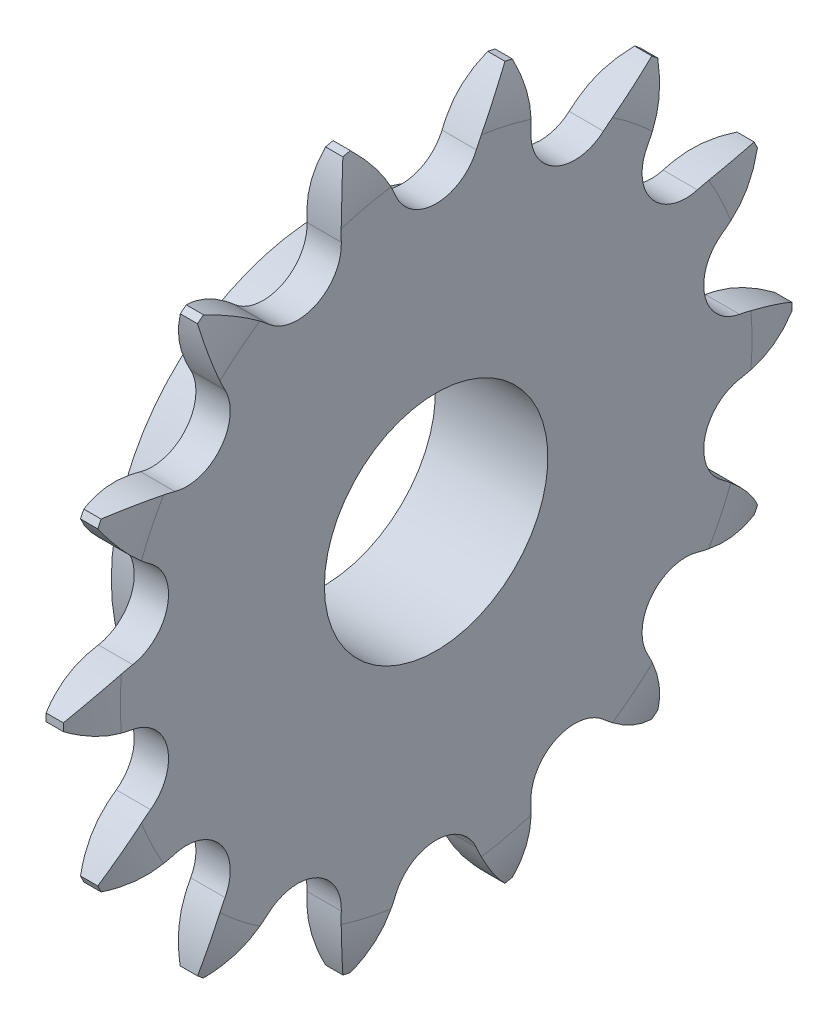
SolidWorks part; units mm, degrees
ref_plane "Plane1" through (0, 0, 0) normal (0, 0, 1) x (1, 0, 0)
ref_plane "Plane2" through (0, 0, 0) normal (0, 1, 0) x (1, 0, 0)
ref_plane "Plane3" through (0, 0, 0) normal (1, 0, 0) x (0, 0, -1)
sketch "Clipboard" plane through (0, 0, 0) normal (0, 1, 0) x (1, 0, 0)
  line L0 (0, 0) -> (12.3228, -3.0724)
  line L1 (-15, 0) -> (100, 0) construction
  line L2 (0, 0) -> (-0.5049, 0.5707)
  line L3 (0, 0) -> (-11.863, 4.5341)
  line L4 (0, 0) -> (3.0079, 0.75)
  line L5 (0, 0) -> (-5.6217, -2.0967)
  line L6 (0, 0) -> (-2.5441, -1.7165)
  line L7 (-0.5049, 0.5707) -> (5.2911, 2.1237)
  line L8 (-76.2, 38.1) -> (-73.4, 38.1)
  line L9 (-73.2427, 39.6204) -> (-72.6435, 39.6525)
  line L10 (-73.1375, 10.4807) -> (-66.1375, 10.4807)
  circle A0 centre (0, 0) radius 3.875
  circle A1 centre (0, 0) radius 19
  circle A2 centre (0, 0) radius 19
  dimension "Dr" = 7.75
  dimension "MHD" = 38
  dimension "Hub_dia" = 38
  dimension "Num_teeth" = 14
  dimension "Pitch" = 12.7
  dimension "Width" = 3.1
  dimension "Side_relief" = 0.762
  dimension "Side_radius" = 12.7
  dimension "Overall_len" = 6
  dimension "Show_teeth" = 14
  dimension "Thickness" = 3.069
  dimension "OAL" = 6.0005
  dimension "T_dim" = 2.8
  dimension "Fillet_rad" = 0.6
  dimension "Face_width" = 3.069
  dimension "Num_strands" = 1
  dimension "Transv_pitch" = 7
  dimension "Plate_wid" = 9.91
sketch "BasProSke" plane through (0, 0, 0) normal (0, 1, 0) x (1, 0, 0)
  line L0 (-10, 0) -> (60, 0) construction
  line L1 (0, 0) -> (0, 28.2662)
  line L2 (0, 0) -> (3.069, 0)
  line L3 (3.069, 0) -> (3.069, 28.2662)
  line L4 (2.307, 32.5991) -> (0.762, 32.5991)
  arc A0 (0, 28.2662) -> (0.762, 32.5991) centre (12.7, 28.2662) cw
  arc A1 (3.069, 28.2662) -> (2.307, 32.5991) centre (-9.631, 28.2662) ccw
  dimension "Thickness" = 3.069
  dimension "D1" = 12.7
  dimension "G1" = 0.762
  dimension "G2" = 0.762
  dimension "Diameter" = 65.1983
revolve "Base-Revolve" add sketch "BasProSke" angle 360 about L0
sketch "TooCutSke" plane through (0, 0, 0) normal (1, 0, 0) x (0, 0, -1)
  line L0 (0, 28.5754) -> (3.5969, 27.0327) construction
  line L1 (0, 0) -> (0, 107) construction
  line L2 (0, 28.5754) -> (-10, 28.5754) construction
  line L3 (0, 28.5754) -> (-3.5969, 27.0327) construction
  arc A0 (3.5969, 27.0327) -> (7.3646, 32.2694) centre (17.2722, 21.1674) cw
  arc A1 (3.5969, 27.0327) -> (-3.5969, 27.0327) centre (0, 28.5754) cw
  arc A2 (-3.5969, 27.0327) -> (-7.3646, 32.2694) centre (-17.2722, 21.1674) ccw
  arc A3 (7.3646, 32.2694) -> (-7.3646, 32.2694) centre (0, 0) ccw
  dimension "R1" = 3.9137
  dimension "R2" = 14.88
  dimension "Overcut" = 33.0991
  dimension "Seat_radius" = 28.5754
  dimension "X" = 133.571
extrude "ToothCut" cut sketch "TooCutSke" along normal through all
pattern_circular "TeethCuts" count 14 every 25.714 about axis through (-10, 0, 0) along (1, 0, 0) of "ToothCut"
sketch "HubNeaOneSke" plane through (0, 0, 0) normal (-1, 0, 0) x (0, 0, 1)
  circle A0 centre (0, 0) radius 19
  dimension "Diameter" = 38
extrude "HubNearOne" add sketch "HubNeaOneSke" along normal blind 7
fillet "HubNearOneFillet" radius 0.6 1 edges at (0, 0, -19)
sketch "HubNeaBotSke" plane through (0, 0, 0) normal (-1, 0, 0) x (0, 0, 1)
  circle A0 centre (0, 0) radius 19
  dimension "Diameter" = 38
extrude "HubNearBoth" [suppressed] add sketch "HubNeaBotSke" along normal blind 1.4657
fillet "HubNearBothFillet" [suppressed] radius 0.6
ref_plane "FarPln" through (3.069, 0, 0) normal (1, 0, 0) x (0, 0, -1)
sketch "HubFarSke" plane through (3.069, 0, 0) normal (1, 0, 0) x (0, 0, -1)
  circle A0 centre (0, 0) radius 19
  dimension "Diameter" = 38
extrude "HubFar" [suppressed] add sketch "HubFarSke" along normal blind 1.4657
fillet "HubFarFillet" [suppressed] radius 0.6
sketch "BorSke" plane through (0, 0, 0) normal (1, 0, 0) x (0, 0, -1)
  circle A0 centre (0, 0) radius 10
  dimension "Diameter" = 20
extrude "Bore" cut sketch "BorSke" along normal through all both and the other way through all
sketch "KeySke" plane through (0, 0, 0) normal (1, 0, 0) x (0, 0, -1)
  line L0 (-3, 0) -> (-3, 12.8)
  line L1 (-3, 12.8) -> (3, 12.8)
  line L2 (3, 12.8) -> (3, 0)
  line L3 (0, 0) -> (0, 34) construction
  line L4 (-3, 0) -> (3, 0)
  dimension "Offset" = 12.8
  dimension "Width" = 6
extrude "Keyway" [suppressed] cut sketch "KeySke" along normal mid plane 12.001
pattern_circular "Keyway2" [suppressed] count 2 every 90 about axis through (-10, 0, 0) along (1, 0, 0)
equation "' \"Pitch@Clipboard\" = 12.7"
equation "' \"Num_strands@Clipboard\" = 1"
equation "' \"Num_teeth@Clipboard\" = 9"
equation "' \"Hub_dia@Clipboard\" = 50"
equation "' \"Overall_len@Clipboard\" = 3"
equation "' \"Diameter@BorSke\" = 12"
equation "' \"T_dim@Clipboard\" = 1"
equation "' \"Width@KeySke\" = 2"
equation "' \"Dr@Clipboard\" = 8.51"
equation "' \"Face_width@Clipboard\" = 7.2"
equation "' \"Side_radius@Clipboard\" = 12.7"
equation "' \"Side_relief@Clipboard\" = 1.27"
equation "' \"Transv_pitch@Clipboard\" = 13.92"
equation "' \"Show_teeth@Clipboard\" = 9"
equation "' \"Fillet_rad@Clipboard\" = 0.6"
equation "' \"Plate_wid@Clipboard\" = 11.8"
equation "\"Num_teeth@Clipboard\" = int( \"Num_teeth@Clipboard\" )"
equation "\"Num_teeth@Clipboard\" = ((sgn( \"Num_teeth@Clipboard\" - 5.0)+1)*( \"Num_teeth@Clipboard\" - 5.0))/2 +5.0"
equation "\"Num_teeth@Clipboard\" = ((sgn( \"Num_teeth@Clipboard\" - 200.0)-1)*( \"Num_teeth@Clipboard\" - 200.0))/-2 +200.0"
equation "\"MHD@Clipboard\" = \"Pitch@Clipboard\" * (1.0 / tan(3.14159265 / \"Num_teeth@Clipboard\" )) - 1.04 * \"Plate_wid@Clipboard\" - 0.76"
equation "\"Thickness@Clipboard\"  = \"Face_width@Clipboard\" + (\"Num_strands@Clipboard\" - 1) * \"Transv_pitch@Clipboard\""
equation "\"OAL@Clipboard\" = \"Thickness@Clipboard\" + 2 * \"Fillet_rad@Clipboard\" + 1"
equation "\"MHD@Clipboard\" = ((sgn( \"MHD@Clipboard\" - \"Hub_dia@Clipboard\" )-1)*( \"MHD@Clipboard\" - \"Hub_dia@Clipboard\" ))/-2+ \"Hub_dia@Clipboard\""
equation "\"OAL@Clipboard\" = ((sgn( \"OAL@Clipboard\" - \"Overall_len@Clipboard\" )+1)*( \"OAL@Clipboard\" - \"Overall_len@Clipboard\" ))/2 + \"Overall_len@Clipboard\" + 0.0005"
equation "\"Num_teeth@TeethCuts\" = int( \"Show_teeth@Clipboard\" ) + 1"
equation "\"Num_teeth@TeethCuts\" = ((sgn( \"Num_teeth@TeethCuts\" - \"Num_teeth@Clipboard\" )-1)*( \"Num_teeth@TeethCuts\" - \"Num_teeth@Clipboard\" ))/-2+ \"Num_teeth@Clipboard\""
equation "\"Num_teeth@TeethCuts\" = ((sgn( \"Num_teeth@TeethCuts\" - 2.0)+1)*( \"Num_teeth@TeethCuts\" - 2.0))/2 +2.0"
equation "\"Angle@TeethCuts\" = 360.0 / \"Num_teeth@Clipboard\""
equation "\"Seat_radius@TooCutSke\" = ( \"Pitch@Clipboard\" / 2.0) / sin(3.14159265 / \"Num_teeth@Clipboard\" ) - \"Dr@Clipboard\" / 2.0 + \"Dr@Clipboard\" * 0.505"
equation "\"R1@TooCutSke\"  = \"Dr@Clipboard\" * 0.505"
equation "\"X@TooCutSke\" = 140.0 - (90.0 / \"Num_teeth@Clipboard\")"
equation "\"R2@TooCutSke\" = 0.12 * \"Dr@Clipboard\" * ( \"Num_teeth@Clipboard\" + 2.0)"
equation "\"Overcut@TooCutSke\" = 0.5 + 0.625 * \"Pitch@Clipboard\" - 0.5 * \"Dr@Clipboard\"  +  \"Pitch@Clipboard\" / 2.0 / sin(3.14159265 / \"Num_teeth@Clipboard\" )"
equation "\"Diameter@BasProSke\" = 2.0 * ( 0.625 * \"Pitch@Clipboard\" - 0.5 * \"Dr@Clipboard\"  +  \"Pitch@Clipboard\" / 2.0 / sin(3.14159265 / \"Num_teeth@Clipboard\" ))"
equation "\"Thickness@BasProSke\"  = \"Thickness@Clipboard\""
equation "\"G1@BasProSke\" =  \"Side_relief@Clipboard\""
equation "\"G2@BasProSke\" =  \"Side_relief@Clipboard\""
equation "\"D1@BasProSke\" =  \"Side_radius@Clipboard\""
equation "\"Diameter@HubNeaOneSke\" = \"MHD@Clipboard\""
equation "\"Diameter@HubNeaBotSke\" = \"MHD@Clipboard\""
equation "\"Length@HubNearBoth\" = ( \"OAL@Clipboard\" - \"Thickness@BasProSke\" ) / 2.0"
equation "\"D1@HubNearOneFillet\" = \"Fillet_rad@Clipboard\""
equation "\"D1@HubNearBothFillet\" = \"Fillet_rad@Clipboard\""
equation "\"Thickness@FarPln\" = \"Thickness@BasProSke\""
equation "\"Diameter@HubFarSke\" = \"MHD@Clipboard\""
equation "\"Length@HubFar\" = ( \"OAL@Clipboard\" - \"Thickness@BasProSke\" ) / 2.0"
equation "\"D1@HubFarFillet\" = \"Fillet_rad@Clipboard\""
equation "\"D1@Keyway\" = \"OAL@Clipboard\" * 2.0"
equation "\"Offset@KeySke\" = \"T_dim@Clipboard\" + \"Diameter@BorSke\" / 2.0"
